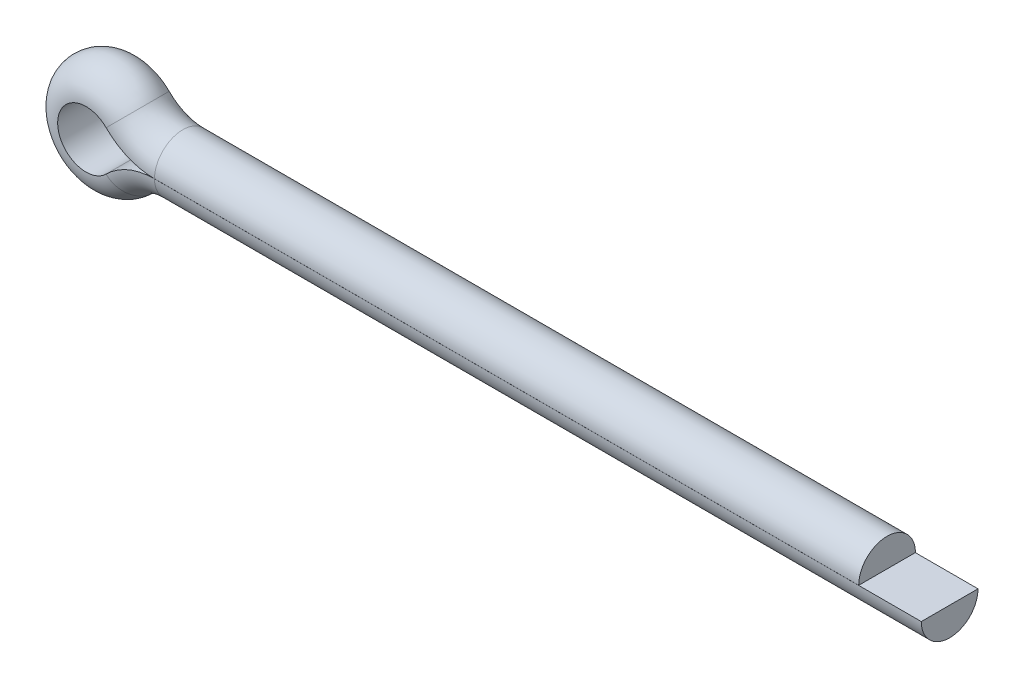
SolidWorks part; units mm, degrees
ref_plane "Front" through (0, 0, 0) normal (0, 0, 1) x (1, 0, 0)
ref_plane "Top" through (0, 0, 0) normal (0, 1, 0) x (1, 0, 0)
ref_plane "Right" through (0, 0, 0) normal (1, 0, 0) x (0, 0, -1)
sketch "PathSke" plane through (0, 0, 0) normal (0, 0, 1) x (1, 0, 0)
  line L0 (36, 1.45) -> (0, 1.45)
  line L1 (0, -1.45) -> (39.2, -1.45)
  line L2 (0, 0) -> (49.7718, 0) construction
  line L3 (0, 0) -> (0, 16.5256) construction
  line L4 (-6.4, 0) -> (-6.4, 13.3379) construction
  arc A0 (0, 1.45) -> (-1.4491, 2.0504) centre (0, 3.4991) cw
  arc A1 (-1.4491, 2.0504) -> (-1.4491, -2.0504) centre (-3.5, 0) ccw
  arc A2 (-1.4491, -2.0504) -> (0, -1.45) centre (0, -3.4991) cw
  dimension "Diameter" = 2.9
  dimension "Head_dia" = 5.8
  dimension "Head_ht" = 6.4
  dimension "Length" = 36
  dimension "Tip_offset" = 3.2
ref_plane "SectionPlane" through (36, 0, 0) normal (1, 0, 0) x (0, 0, -1)
sketch "SectionSke" plane through (36, 0, 0) normal (1, 0, 0) x (0, 0, -1)
  line L1 (-1.45, 0.002) -> (1.45, 0.002)
  arc A0 (1.45, 0.002) -> (-1.45, 0.002) centre (0, 0) ccw
  dimension "Diameter" = 2.9
  dimension "D1" = 0.002
sweep "Body" add profiles "SectionSke" path "PathSke"
sketch "ConeCutSke" plane through (0, 0, 0) normal (0, 0, 1) x (1, 0, 0)
  line L0 (0, 0) -> (0, 16.2682) construction
  line L1 (0, 0) -> (75.9079, 0) construction
  line L2 (0, 0) -> (39.2, 0) construction
  line L3 (36, 0.726) -> (34.9603, 1.46)
  line L4 (36, 0.002) -> (36, 1.45) construction
  line L6 (36, 0.726) -> (34.9547, 0)
  line L7 (39.2, -0.726) -> (38.1547, 0)
  line L8 (39.2, -1.45) -> (39.2, -0.002) construction
  line L9 (39.2, -0.726) -> (38.1603, -1.46)
  line L10 (38.1547, 0) -> (34.9547, 0)
  line L11 (34.9603, 1.46) -> (39.21, 1.46)
  line L12 (39.21, 1.46) -> (39.21, -1.46)
  line L13 (39.21, -1.46) -> (38.1603, -1.46)
  line L14 (36, 1.45) -> (0, 1.45) construction
  dimension "D1" = 0.01
  dimension "D2" = 0.01
  dimension "D3" = 70
  dimension "D4" = 70
extrude "ConeCut" [suppressed] cut sketch "ConeCutSke" against normal through all and the other way through all
equation "' \"Diameter@PathSke\" = 9.5"
equation "' \"Head_dia@PathSke\" = 19"
equation "' \"Head_ht@PathSke\" = 20"
equation "' \"Tip_offset@PathSke\" = 6.3"
equation "' \"Length@PathSke\" = 45"
equation "' \"Diameter@PathSke\" = 1"
equation "' \"Head_dia@PathSke\" = 2"
equation "' \"Head_ht@PathSke\" = 3"
equation "' \"Tip_offset@PathSke\" = 2.5"
equation "' \"Length@PathSke\" = 8"
equation "' \"Diameter@PathSke\" = 0.5"
equation "' \"Head_dia@PathSke\" = 1"
equation "' \"Head_ht@PathSke\" = 2"
equation "' \"Tip_offset@PathSke\" = 1.6"
equation "' \"Length@PathSke\" = 4"
equation "\"Diameter@SectionSke\" = \"Diameter@PathSke\""
equation "\"Length@SectionPlane\" = \"Length@PathSke\""
